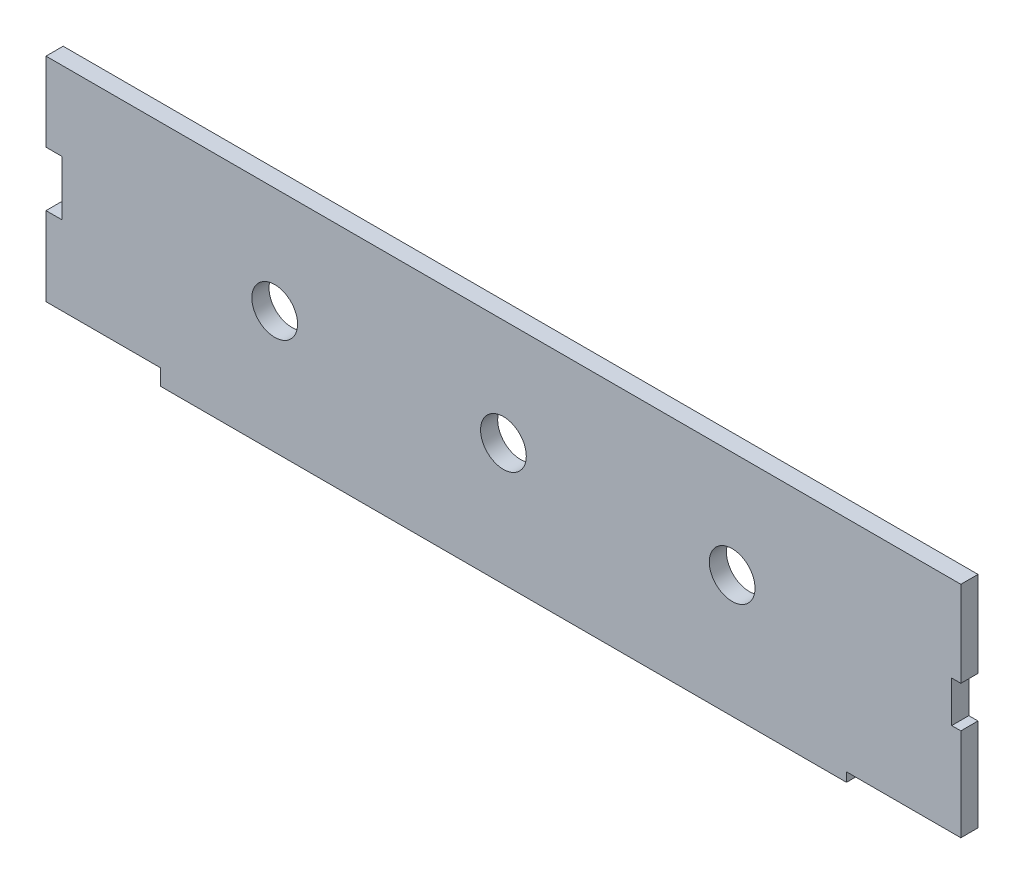
SolidWorks part; units mm, degrees
ref_plane "Alzado" through (0, 0, 0) normal (0, 0, 1) x (1, 0, 0)
ref_plane "Planta" through (0, 0, 0) normal (0, 1, 0) x (1, 0, 0)
ref_plane "Vista lateral" through (0, 0, 0) normal (1, 0, 0) x (0, 0, -1)
sketch "Croquis1" plane through (0, 0, 0) normal (0, 0, 1) x (1, 0, 0)
  line L0 (-40, 9.3) -> (40, 9.3)
  line L1 (40, 9.3) -> (40, 1.8)
  line L2 (40, 1.8) -> (39.2, 1.8)
  line L3 (39.2, 1.8) -> (39.2, -1.8)
  line L4 (39.2, -1.8) -> (40, -1.8)
  line L5 (40, -1.8) -> (40, -9.9)
  line L6 (40, -9.9) -> (30, -9.9)
  line L7 (30, -9.9) -> (30, -10.7)
  line L8 (30, -10.7) -> (-30, -10.7)
  line L9 (-30, -10.7) -> (-30, -9.3)
  line L10 (-30, -9.3) -> (-40, -9.3)
  line L11 (-40, -9.3) -> (-40, -2.4)
  line L12 (-40, -2.4) -> (-38.6, -2.4)
  line L13 (-38.6, -2.4) -> (-38.6, 2.4)
  line L14 (-38.6, 2.4) -> (-40, 2.4)
  line L15 (-40, 2.4) -> (-40, 9.3)
  line L16 (39.2, 0) -> (-38.6, 0) construction
  circle A0 centre (20, 0) radius 2
  circle A1 centre (0, 0) radius 2
  circle A2 centre (-20, 0) radius 2
  point P16 (-38.6, 0)
  point P18 (39.2, 0)
  point P19 (0, 9.3)
  dimension "D9" = 4
  dimension "D10" = 20
  dimension "D11" = 20
  dimension "D12" = 20
  dimension "D1" = 80
  dimension "D2" = 10
  dimension "D3" = 10
  dimension "D4" = 20
  dimension "D5" = 4.8
  dimension "D6" = 3.6
  dimension "D7" = 1.4
  dimension "D8" = 0.8
extrude "Saliente-Extruir1" add sketch "Croquis1" along normal blind 1.5
